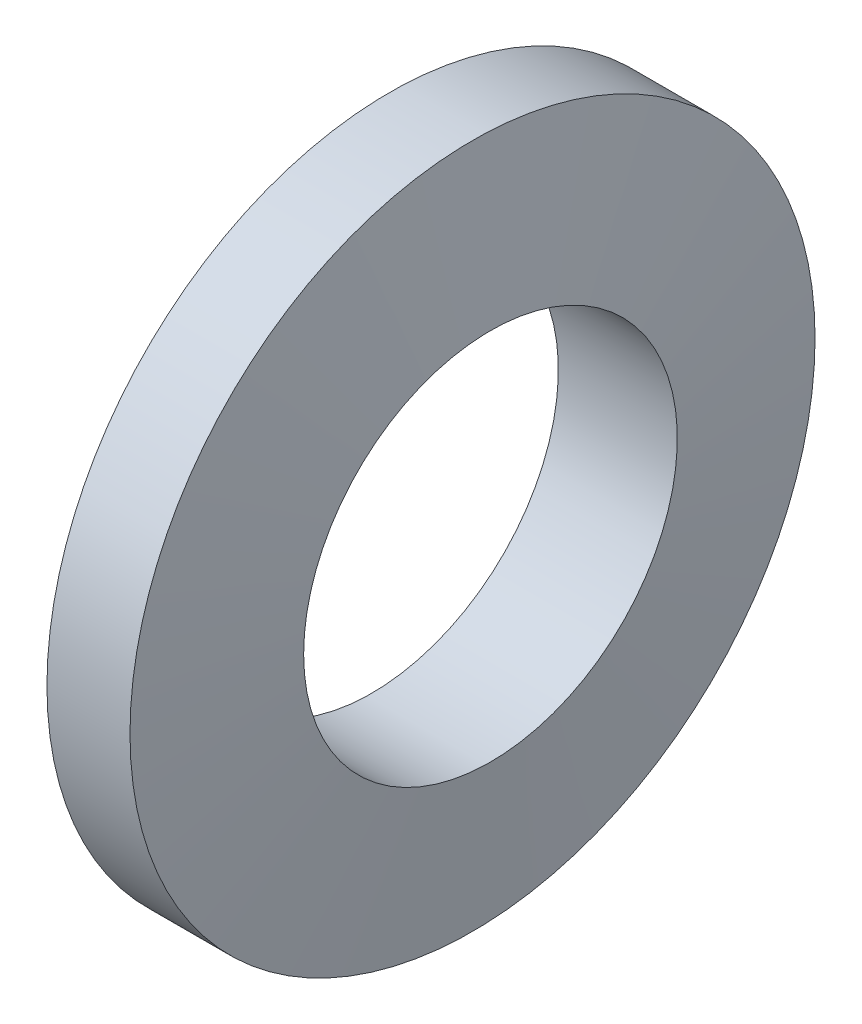
SolidWorks part; units mm, degrees
material "非常高密度 PE (SS)"
ref_plane "前视基准面" through (0, 0, 0) normal (0, 0, 1) x (1, 0, 0)
ref_plane "上视基准面" through (0, 0, 0) normal (0, 1, 0) x (1, 0, 0)
ref_plane "右视基准面" through (0, 0, 0) normal (1, 0, 0) x (0, 0, -1)
sketch "草图2" plane through (0, 0, 0) normal (0, 0, 1) x (1, 0, 0)
  line L0 (0, 23.8559) -> (0, 0) construction
  line L1 (0, 0) -> (39.6943, 0) construction
  line L2 (-2, 16.5) -> (2, 16.5)
  line L3 (2, 16.5) -> (2.8654, 9)
  line L4 (2.8654, 9) -> (-2.8654, 9)
  line L5 (-2.75, 10) -> (2.75, 10) construction
  line L6 (-2, 16.5) -> (-2.8654, 9)
  point P11 (0, 9)
  point P12 (0, 10)
  point P13 (0, 16.5)
  dimension "D1" = 18
  dimension "D2" = 10
  dimension "D3" = 33
  dimension "D4" = 4
  dimension "D5" = 5.5
revolve "旋转1" add sketch "草图2" angle 360 about L1
